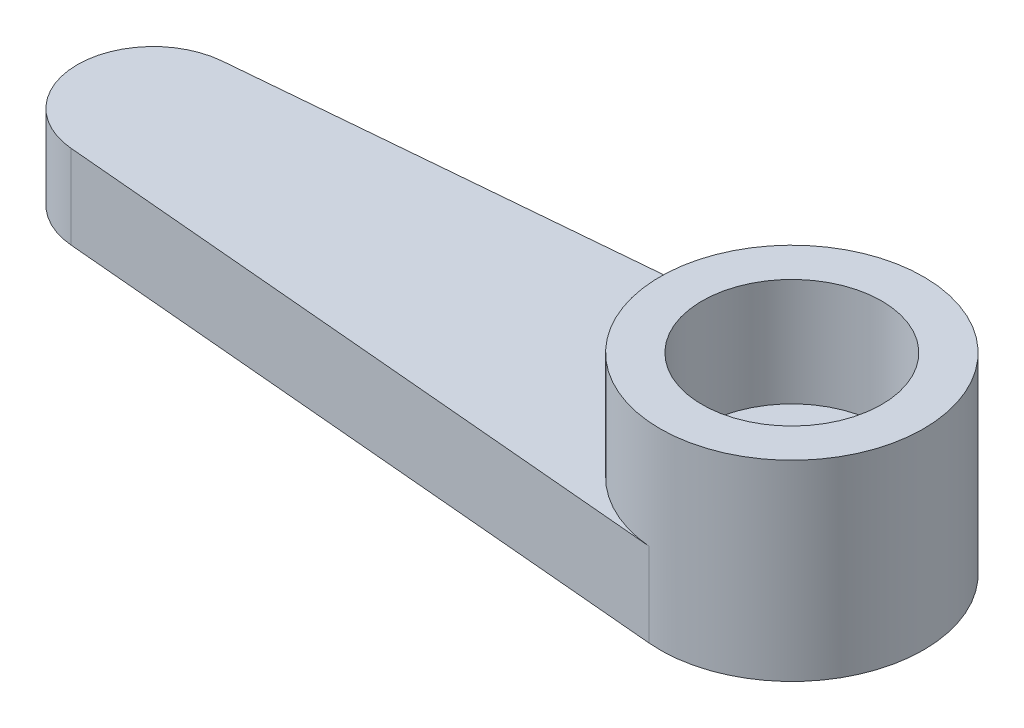
SolidWorks part; units mm, degrees
ref_plane "前视基准面" through (0, 0, 0) normal (0, 0, 1) x (1, 0, 0)
ref_plane "上视基准面" through (0, 0, 0) normal (0, 1, 0) x (1, 0, 0)
ref_plane "右视基准面" through (0, 0, 0) normal (1, 0, 0) x (0, 0, -1)
sketch "草图2" plane through (0, 0, 0) normal (0, 1, 0) x (1, 0, 0)
  line L0 (0, 0) -> (-13.6109, 0) construction
  line L1 (-16.1663, 1.8927) -> (-0.2888, 3.2873)
  line L2 (-16.1663, -1.8927) -> (-0.2887, -3.2873)
  arc A0 (-0.2887, -3.2873) -> (-0.2888, 3.2873) centre (0, 0) ccw
  arc A1 (-16.1663, 1.8927) -> (-16.1663, -1.8927) centre (-16, 0) ccw
  dimension "D1" = 6.6
  dimension "D2" = 3.8
  dimension "D3" = 16
extrude "凸台-拉伸1" add sketch "草图2" along normal blind 2.1
sketch "草图3" plane through (0, 2.1, 0) normal (0, 1, 0) x (1, 0, 0)
  circle A0 centre (0, 0) radius 3.3
  circle A1 centre (0, 0) radius 2.25
  dimension "D1" = 4.5
extrude "凸台-拉伸2" add sketch "草图3" along normal blind 2.7
sketch "草图5" plane through (0, 2.1, 0) normal (0, 1, 0) x (1, 0, 0)
  circle A0 centre (0, 0) radius 1.2
  dimension "D1" = 2.4
extrude "切除-拉伸1" cut sketch "草图5" against normal blind 2.7
